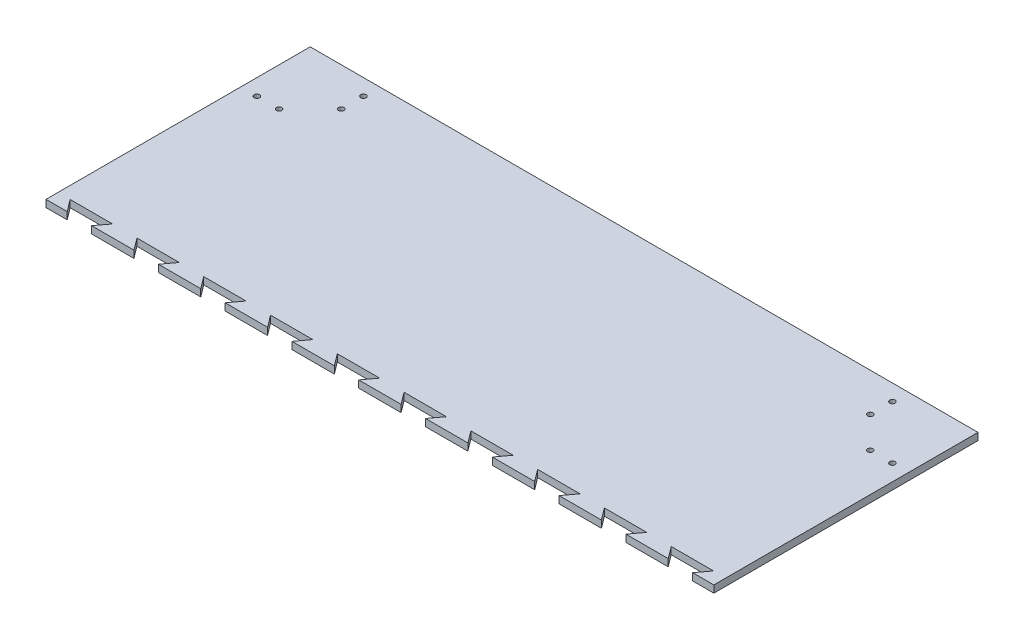
SolidWorks part; units mm, degrees
material "Multistrato di pioppo"
ref_plane "Piano frontale" through (0, 0, 0) normal (0, 0, 1) x (1, 0, 0)
ref_plane "Piano superiore" through (0, 0, 0) normal (0, 1, 0) x (1, 0, 0)
ref_plane "Piano destro" through (0, 0, 0) normal (1, 0, 0) x (0, 0, -1)
sketch "Schizzo1" plane through (0, 0, 0) normal (0, 1, 0) x (1, 0, 0)
  line L1 (-279, 220.75) -> (279, 220.75)
  line L2 (-279, 220.75) -> (-279, -220.75)
  line L3 (-279, -220.75) -> (279, -220.75)
  line L4 (279, 220.75) -> (279, -220.75)
  line L5 (-279, 220.75) -> (279, -220.75) construction
  line L6 (-279, -220.75) -> (279, 220.75) construction
  point P4 (0, 0)
  dimension "D1" = 558
  dimension "D2" = 441.5
extrude "Estrusione-Estrusione1" add sketch "Schizzo1" along normal blind 6
sketch "Schizzo2" plane through (0, 0, 0) normal (0, -1, 0) x (-1, 0, 0)
  circle A0 centre (-221, 207.25) radius 2.25
  circle A1 centre (-221, 188.75) radius 2.25
  circle A2 centre (-247, 162.75) radius 2.25
  circle A3 centre (-265.5, 162.75) radius 2.25
  circle A4 centre (221, 207.25) radius 2.25
  circle A5 centre (221, 188.75) radius 2.25
  circle A6 centre (247, 162.75) radius 2.25
  circle A7 centre (265.5, 162.75) radius 2.25
  circle A8 centre (265.5, -162.75) radius 2.25
  circle A9 centre (247, -162.75) radius 2.25
  circle A10 centre (-265.5, -162.75) radius 2.25
  circle A11 centre (-247, -162.75) radius 2.25
  circle A12 centre (-87.5, -195.25) radius 2.25
  dimension "D1" = 4.5
extrude "Taglio-Estrusione1" cut sketch "Schizzo2" against normal blind 10
sketch "Schizzo3" plane through (0, 6, 0) normal (0, 1, 0) x (1, 0, 0)
  line L0 (-279, 0) -> (-261.3, 0)
  line L1 (-279, 220.75) -> (-279, -220.75) construction
  line L2 (-261.3, 0) -> (-268.8, 10)
  line L3 (-268.8, 10) -> (-233.4, 10)
  line L4 (-233.4, 10) -> (-240.9, 0)
  line L5 (-240.9, 0) -> (-223.2, 0)
  line L6 (-261.3, 0) -> (-240.9, 0) construction
  line L7 (-251.1, 0) -> (-251.1, 10) construction
  line L8 (-279, 0) -> (-279, -220.75)
  line L9 (-279, -220.75) -> (279, -220.75)
  line L10 (-223.2, 0) -> (-205.5, 0)
  line L11 (-205.5, 0) -> (-213, 10)
  line L12 (-213, 10) -> (-177.6, 10)
  line L13 (-177.6, 10) -> (-185.1, 0)
  line L14 (-185.1, 0) -> (-167.4, 0)
  line L15 (-205.5, 0) -> (-185.1, 0) construction
  line L16 (-195.3, 0) -> (-195.3, 10) construction
  line L17 (-167.4, 0) -> (-149.7, 0)
  line L18 (-149.7, 0) -> (-157.2, 10)
  line L19 (-157.2, 10) -> (-121.8, 10)
  line L20 (-121.8, 10) -> (-129.3, 0)
  line L21 (-129.3, 0) -> (-111.6, 0)
  line L22 (-149.7, 0) -> (-129.3, 0) construction
  line L23 (-139.5, 0) -> (-139.5, 10) construction
  line L24 (-111.6, 0) -> (-93.9, 0)
  line L25 (-93.9, 0) -> (-101.4, 10)
  line L26 (-101.4, 10) -> (-66, 10)
  line L27 (-66, 10) -> (-73.5, 0)
  line L28 (-73.5, 0) -> (-55.8, 0)
  line L29 (-93.9, 0) -> (-73.5, 0) construction
  line L30 (-83.7, 0) -> (-83.7, 10) construction
  line L31 (-55.8, 0) -> (-38.1, 0)
  line L32 (-38.1, 0) -> (-45.6, 10)
  line L33 (-45.6, 10) -> (-10.2, 10)
  line L34 (-10.2, 10) -> (-17.7, 0)
  line L35 (-17.7, 0) -> (0, 0)
  line L36 (-38.1, 0) -> (-17.7, 0) construction
  line L37 (-27.9, 0) -> (-27.9, 10) construction
  line L38 (0, 0) -> (17.7, 0)
  line L39 (17.7, 0) -> (10.2, 10)
  line L40 (10.2, 10) -> (45.6, 10)
  line L41 (45.6, 10) -> (38.1, 0)
  line L42 (38.1, 0) -> (55.8, 0)
  line L43 (17.7, 0) -> (38.1, 0) construction
  line L44 (27.9, 0) -> (27.9, 10) construction
  line L45 (55.8, 0) -> (73.5, 0)
  line L46 (73.5, 0) -> (66, 10)
  line L47 (66, 10) -> (101.4, 10)
  line L48 (101.4, 10) -> (93.9, 0)
  line L49 (93.9, 0) -> (111.6, 0)
  line L50 (73.5, 0) -> (93.9, 0) construction
  line L51 (83.7, 0) -> (83.7, 10) construction
  line L52 (111.6, 0) -> (129.3, 0)
  line L53 (129.3, 0) -> (121.8, 10)
  line L54 (121.8, 10) -> (157.2, 10)
  line L55 (157.2, 10) -> (149.7, 0)
  line L56 (149.7, 0) -> (167.4, 0)
  line L57 (129.3, 0) -> (149.7, 0) construction
  line L58 (139.5, 0) -> (139.5, 10) construction
  line L59 (167.4, 0) -> (185.1, 0)
  line L60 (185.1, 0) -> (177.6, 10)
  line L61 (177.6, 10) -> (213, 10)
  line L62 (213, 10) -> (205.5, 0)
  line L63 (205.5, 0) -> (223.2, 0)
  line L64 (185.1, 0) -> (205.5, 0) construction
  line L65 (195.3, 0) -> (195.3, 10) construction
  line L66 (223.2, 0) -> (240.9, 0)
  line L67 (240.9, 0) -> (233.4, 10)
  line L68 (233.4, 10) -> (268.8, 10)
  line L69 (268.8, 10) -> (261.3, 0)
  line L70 (261.3, 0) -> (279, 0)
  line L71 (240.9, 0) -> (261.3, 0) construction
  line L72 (251.1, 0) -> (251.1, 10) construction
  line L73 (279, -220.75) -> (279, 220.75) construction
  line L74 (279, -220.75) -> (279, 0)
  dimension "D1" = 55.8
  dimension "D2" = 35.4
  dimension "D3" = 20.4
  dimension "D4" = 10
  dimension "D5" = 10
extrude "Taglio-Estrusione2" cut sketch "Schizzo3" against normal blind 10
